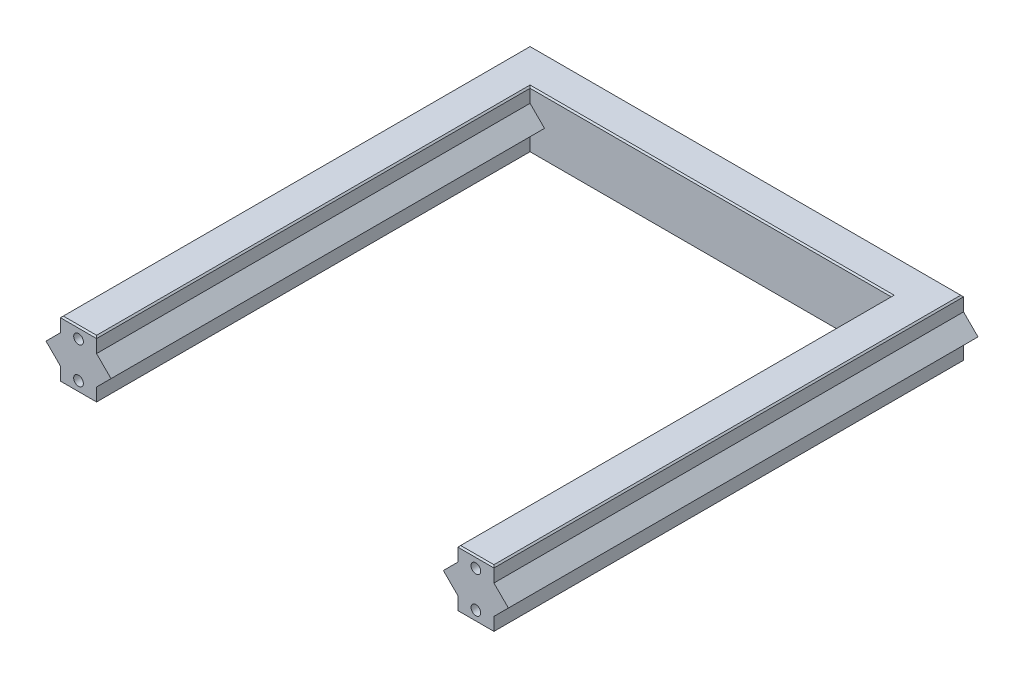
SolidWorks part; units mm, degrees
ref_plane "Front Plane" through (0, 0, 0) normal (0, 0, 1) x (1, 0, 0)
ref_plane "Top Plane" through (0, 0, 0) normal (0, 1, 0) x (1, 0, 0)
ref_plane "Right Plane" through (0, 0, 0) normal (1, 0, 0) x (0, 0, -1)
sketch "Sketch2" plane through (0, 0, 0) normal (0, 0, 1) x (1, 0, 0)
  line L0 (-76.2, 5.08) -> (-81.28, 0)
  line L1 (-76.2, 10.16) -> (76.2, 10.16)
  line L2 (-76.2, 10.16) -> (-76.2, 5.08)
  line L3 (-76.2, -10.16) -> (76.2, -10.16)
  line L4 (76.2, 10.16) -> (76.2, 5.08)
  line L5 (-76.2, 10.16) -> (76.2, -10.16) construction
  line L6 (-76.2, -10.16) -> (76.2, 10.16) construction
  line L7 (-81.28, 0) -> (-76.2, -5.08)
  line L8 (-76.2, -5.08) -> (-76.2, -10.16)
  line L9 (0, 10.16) -> (0, -10.16) construction
  line L10 (81.28, 0) -> (76.2, -5.08)
  line L11 (76.2, 5.08) -> (81.28, 0)
  line L12 (76.2, -5.08) -> (76.2, -10.16)
  point P0 (0, 0)
  dimension "D1" = 152.4
  dimension "D2" = 20.32
  dimension "D3" = 10.16
extrude "Boss-Extrude1" add sketch "Sketch2" along normal blind 12.7
sketch "Sketch3" plane through (0, 0, 12.7) normal (0, 0, 1) x (1, 0, 0)
  line L0 (-76.2, -10.16) -> (76.2, -10.16) construction
  line L1 (-76.2, 10.16) -> (-63.5, 10.16)
  line L2 (-76.2, 10.16) -> (-76.2, 5.08)
  line L3 (-76.2, -10.16) -> (-63.5, -10.16)
  line L4 (-63.5, 10.16) -> (-63.5, 5.08)
  line L5 (0, 10.16) -> (0, -10.16) construction
  line L6 (76.2, 10.16) -> (-76.2, 10.16) construction
  line L7 (63.5, 10.16) -> (63.5, 5.08)
  line L8 (76.2, -10.16) -> (63.5, -10.16)
  line L9 (76.2, 10.16) -> (76.2, 5.08)
  line L10 (76.2, 10.16) -> (63.5, 10.16)
  line L11 (-63.5, 5.08) -> (-58.42, 0)
  line L12 (-58.42, 0) -> (-63.5, -5.08)
  line L13 (58.42, 0) -> (63.5, -5.08)
  line L14 (63.5, 5.08) -> (58.42, 0)
  line L15 (-63.5, -5.08) -> (-63.5, -10.16)
  line L16 (63.5, -5.08) -> (63.5, -10.16)
  line L17 (-81.28, 0) -> (-76.2, -5.08) construction
  line L18 (-76.2, 5.08) -> (-81.28, 0) construction
  line L19 (-81.28, 0) -> (-76.2, -5.08)
  line L20 (-76.2, 5.08) -> (-81.28, 0)
  line L21 (81.28, 0) -> (76.2, 5.08) construction
  line L22 (76.2, -5.08) -> (81.28, 0) construction
  line L23 (81.28, 0) -> (76.2, 5.08)
  line L24 (76.2, -5.08) -> (81.28, 0)
  line L25 (76.2, -5.08) -> (76.2, -10.16)
  line L26 (-76.2, -5.08) -> (-76.2, -10.16)
  dimension "D1" = 12.7
  dimension "D2" = 10.16
extrude "Boss-Extrude2" add sketch "Sketch3" along normal blind 152.4
sketch "Sketch4" plane through (0, 0, 165.1) normal (0, 0, 1) x (1, 0, 0)
  line L0 (-81.28, 0) -> (-58.42, 0) construction
  line L1 (0, 10.16) -> (0, -10.16) construction
  line L2 (63.5, 10.16) -> (-63.5, 10.16) construction
  line L3 (-63.5, -10.16) -> (63.5, -10.16) construction
  line L4 (-76.2, 10.16) -> (76.2, 10.16)
  line L5 (76.2, -10.16) -> (-76.2, -10.16)
  line L6 (76.2, -10.16) -> (76.2, -5.08) construction
  line L7 (76.2, -5.08) -> (81.28, 0) construction
  line L8 (81.28, 0) -> (76.2, 5.08) construction
  line L9 (76.2, 5.08) -> (76.2, 10.16) construction
  line L10 (-76.2, -5.08) -> (-76.2, -10.16) construction
  line L11 (-81.28, 0) -> (-76.2, -5.08) construction
  line L12 (76.2, -10.16) -> (76.2, -5.08)
  line L13 (76.2, -5.08) -> (81.28, 0)
  line L14 (81.28, 0) -> (76.2, 5.08)
  line L15 (76.2, 5.08) -> (76.2, 10.16)
  line L16 (-76.2, -5.08) -> (-76.2, -10.16)
  line L17 (-81.28, 0) -> (-76.2, -5.08)
  line L18 (-81.28, 0) -> (-76.2, 5.08)
  line L19 (-76.2, 5.08) -> (-81.28, 0) construction
  line L20 (-76.2, 5.08) -> (-76.2, 10.16)
  circle A0 centre (-69.85, 6.35) radius 3.5 construction
  point P0 (-69.85, 6.35)
  point P5 (-69.85, -6.35)
  point P12 (69.85, -6.35)
  point P13 (69.85, 6.35)
  point P17 (-69.85, 0)
  dimension "D2" = 7
  dimension "D1" = 6.35
hole_wizard "#6-32 Tapped Hole1" positions "Sketch5" profile "Sketch7" tap size "#6-32" standard "ANSI Inch" end condition through all
sketch "Sketch5" plane through (0, 0, 165.1) normal (0, 0, 1) x (1, 0, 0)
  point P0 (-69.85, 6.35)
  point P3 (-69.85, -6.35)
  point P6 (69.85, 6.35)
  point P9 (69.85, -6.35)
cosmetic thread "Hole Thread1" parameters "D2"=3.5052
cosmetic thread "Hole Thread2" parameters "D2"=3.5052
cosmetic thread "Hole Thread3" parameters "D2"=3.5052
cosmetic thread "Hole Thread4" parameters "D2"=3.5052
sketch "Sketch7" plane through (-69.85, 6.35, 165.1) normal (1, 0, 0) x (0, -1, 0)
  line L0 (0, 0) -> (0, 165.1)
  line L1 (0, 165.1) -> (1.7, 165.1)
  line L2 (1.7, 165.1) -> (1.7, 0)
  line L5 (1.7, 0) -> (0, 0)
  line L11 (0, -6.35) -> (0, 107.95) construction
  dimension "Thru Tap Drill Dia." = 3.4
  dimension "Thru Tap Drill Depth" = 165.1
chamfer "Chamfer1" distance 0.5 angle 45 16 edges at (-76.2, -10.16, 82.55) (-69.85, -10.16, 165.1) (-63.5, -10.16, 88.9) (0, -10.16, 12.7) (63.5, -10.16, 88.9) (69.85, -10.16, 165.1) (76.2, -10.16, 82.55) (0, -10.16, 0) (76.2, 10.16, 82.55) (69.85, 10.16, 165.1) (63.5, 10.16, 88.9) (0, 10.16, 12.7) (-63.5, 10.16, 88.9) (-69.85, 10.16, 165.1) (-76.2, 10.16, 82.55) (0, 10.16, 0)
